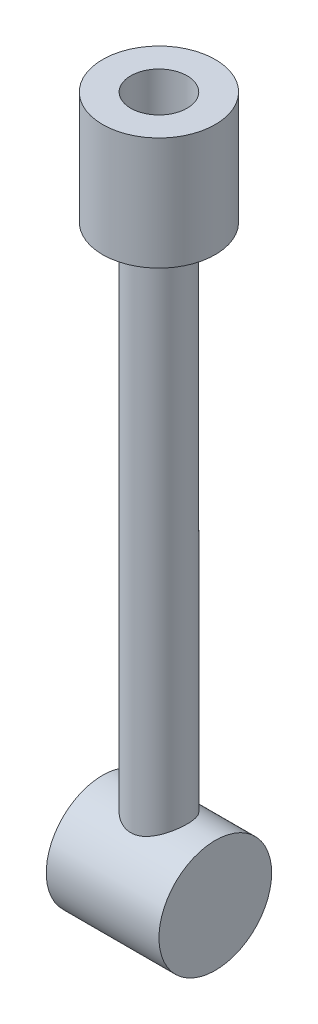
SolidWorks part; units mm, degrees
ref_plane "Front" through (0, 0, 0) normal (0, 0, 1) x (1, 0, 0)
ref_plane "Top" through (0, 0, 0) normal (0, 1, 0) x (1, 0, 0)
ref_plane "Right" through (0, 0, 0) normal (1, 0, 0) x (0, 0, -1)
sketch "Croquis1" plane through (0, 0, 0) normal (1, 0, 0) x (0, 0, -1)
  circle A0 centre (0, 0) radius 50
  dimension "D1" = 100
extrude "Saliente-Extruir1" add sketch "Croquis1" along normal mid plane 100
sketch "Croquis2" plane through (0, 0, 0) normal (0, 1, 0) x (1, 0, 0)
  circle A0 centre (0, 0) radius 25
  dimension "D1" = 50
extrude "Saliente-Extruir2" add sketch "Croquis2" along normal blind 500
sketch "Croquis3" plane through (0, 500, 0) normal (0, 1, 0) x (1, 0, 0)
  circle A0 centre (0, 0) radius 50
  dimension "D1" = 100
extrude "Saliente-Extruir3" add sketch "Croquis3" along normal blind 100
sketch "Croquis4" plane through (0, 600, 0) normal (0, 1, 0) x (1, 0, 0)
  circle A0 centre (0, 0) radius 25
  dimension "D1" = 50
extrude "Cortar-Extruir1" cut sketch "Croquis4" against normal blind 50
